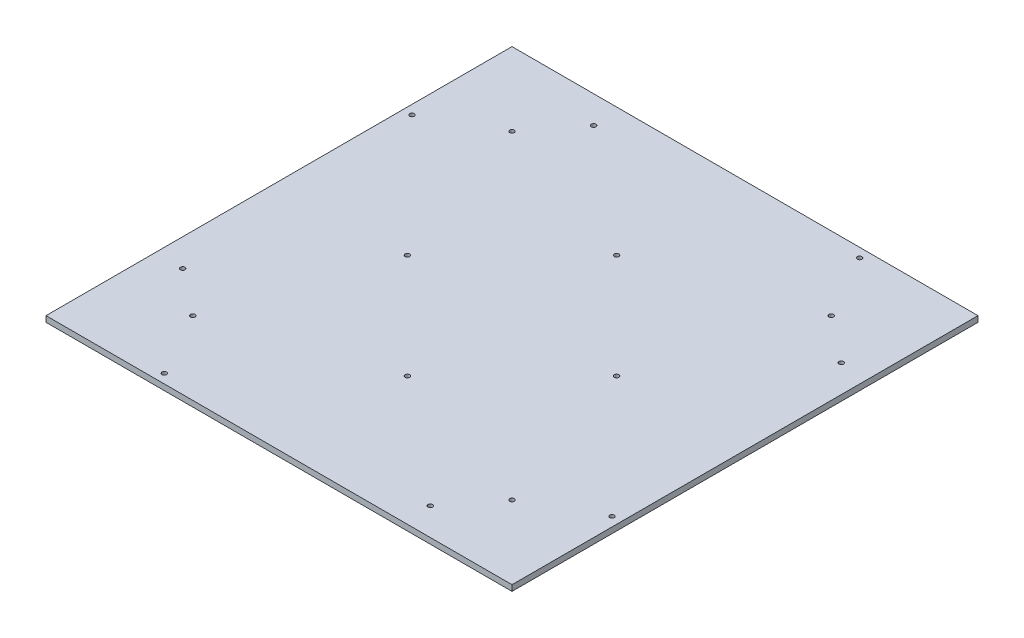
SolidWorks part; units mm, degrees
material "Polyetheretherketone (PEEK)"
ref_plane "Front Plane" through (0, 0, 0) normal (0, 0, 1) x (1, 0, 0)
ref_plane "Top Plane" through (0, 0, 0) normal (0, 1, 0) x (1, 0, 0)
ref_plane "Right Plane" through (0, 0, 0) normal (1, 0, 0) x (0, 0, -1)
sketch "Sketch1" plane through (0, 0, 0) normal (0, 1, 0) x (1, 0, 0)
  line L1 (-127, -127) -> (127, -127)
  line L2 (-127, -127) -> (-127, 127)
  line L3 (-127, 127) -> (127, 127)
  line L4 (127, -127) -> (127, 127)
  line L5 (-127, -127) -> (127, 127) construction
  line L6 (-127, 127) -> (127, -127) construction
  point P0 (0, 0)
  dimension "D1" = 254
extrude "Boss-Extrude1" add sketch "Sketch1" along normal mid plane 3.175
sketch "Sketch2" plane through (0, 1.5875, 0) normal (0, 1, 0) x (1, 0, 0)
  line L0 (-67.5, -127) -> (-67.5, -122) construction
  line L1 (-127, -127) -> (127, -127) construction
  line L2 (67.5, -127) -> (67.5, -112) construction
  line L3 (-127, 127) -> (-127, -127) construction
  line L4 (127, -127) -> (127, 127) construction
  line L5 (-127, 67.5) -> (-122, 67.5) construction
  line L6 (-127, -67.5) -> (-112, -67.5) construction
  line L7 (67.5, 127) -> (67.5, 122) construction
  line L8 (-67.5, 127) -> (-67.5, 112) construction
  line L9 (127, -67.5) -> (122, -67.5) construction
  line L10 (127, 67.5) -> (112, 67.5) construction
  line L11 (127, 127) -> (-127, 127) construction
  point P25 (0, 0)
  dimension "D1" = 59.5
  dimension "D2" = 59.5
  dimension "D3" = 15
  dimension "D4" = 5
  dimension "D5" = 4
hole_wizard "M3x0.5 Tapped Hole1" positions "Sketch3" profile "Sketch4" tap size "M3x0.5" standard "ANSI Metric" end condition through all
sketch "Sketch3" plane through (0, 1.5875, 0) normal (0, 1, 0) x (1, 0, 0)
  point P0 (112, 67.5)
  point P3 (67.5, 122)
  point P6 (-67.5, 112)
  point P9 (-122, 67.5)
  point P12 (-112, -67.5)
  point P15 (-67.5, -122)
  point P18 (67.5, -112)
  point P21 (122, -67.5)
sketch "Sketch4" plane through (112, 1.5875, -67.5) normal (1, 0, 0) x (0, 0, 1)
  line L0 (0, 0) -> (0, 3.175)
  line L1 (0, 3.175) -> (1.25, 3.175)
  line L2 (1.25, 3.175) -> (1.25, 0)
  line L5 (1.25, 0) -> (0, 0)
  line L11 (0, -6.35) -> (0, 107.95) construction
  dimension "Thru Tap Drill Dia." = 2.5
  dimension "Thru Tap Drill Depth" = 3.175
cosmetic thread "Hole Thread1" parameters "D2"=3
cosmetic thread "Hole Thread2" parameters "D2"=3
cosmetic thread "Hole Thread3" parameters "D2"=3
cosmetic thread "Hole Thread4" parameters "D2"=3
cosmetic thread "Hole Thread5" parameters "D2"=3
cosmetic thread "Hole Thread6" parameters "D2"=3
cosmetic thread "Hole Thread7" parameters "D2"=3
cosmetic thread "Hole Thread8" parameters "D2"=3
sketch "Sketch5" plane through (0, 1.5875, 0) normal (0, 1, 0) x (1, 0, 0)
  line L0 (0, 57) -> (0, -57)
  line L1 (-57, 0) -> (57, 0)
  line L2 (127, -127) -> (127, 127) construction
  line L3 (-87, -87) -> (87, -87)
  line L4 (-87, -87) -> (-87, 87)
  line L5 (-87, 87) -> (87, 87)
  line L6 (87, -87) -> (87, 87)
  line L7 (-87, -87) -> (87, 87) construction
  line L8 (-87, 87) -> (87, -87) construction
  line L9 (-127, 127) -> (-127, -127) construction
  line L10 (-127, -127) -> (127, -127) construction
  point P5 (0, 0)
  point P12 (0, 0)
  point P15 (0, -52.4786)
  dimension "D1" = 174
  dimension "D2" = 70
  dimension "D3" = 70
  dimension "D4" = 70
hole_wizard "M3x0.5 Tapped Hole3" positions "Sketch8" profile "Sketch9" tap size "M3x0.5" standard "ANSI Metric" end condition through all
sketch "Sketch8" plane through (0, 1.5875, 0) normal (0, 1, 0) x (1, 0, 0)
  point P0 (0, 57)
  point P3 (-57, 0)
  point P6 (0, -57)
  point P9 (57, 0)
  point P12 (87, 87)
  point P15 (-87, 87)
  point P18 (-87, -87)
  point P21 (87, -87)
sketch "Sketch9" plane through (0, 1.5875, -57) normal (1, 0, 0) x (0, 0, 1)
  line L0 (0, 0) -> (0, 3.175)
  line L1 (0, 3.175) -> (1.25, 3.175)
  line L2 (1.25, 3.175) -> (1.25, 0)
  line L5 (1.25, 0) -> (0, 0)
  line L11 (0, -6.35) -> (0, 107.95) construction
  dimension "Thru Tap Drill Dia." = 2.5
  dimension "Thru Tap Drill Depth" = 3.175
cosmetic thread "Hole Thread17" parameters "D2"=3
cosmetic thread "Hole Thread18" parameters "D2"=3
cosmetic thread "Hole Thread19" parameters "D2"=3
cosmetic thread "Hole Thread20" parameters "D2"=3
cosmetic thread "Hole Thread21" parameters "D2"=3
cosmetic thread "Hole Thread22" parameters "D2"=3
cosmetic thread "Hole Thread23" parameters "D2"=3
cosmetic thread "Hole Thread24" parameters "D2"=3
equation "\"D2@Sketch2\"=\"D1@Sketch2\""
equation "\"D3@Sketch5\"=\"D2@Sketch5\""
equation "\"D4@Sketch5\"=\"D2@Sketch5\""
